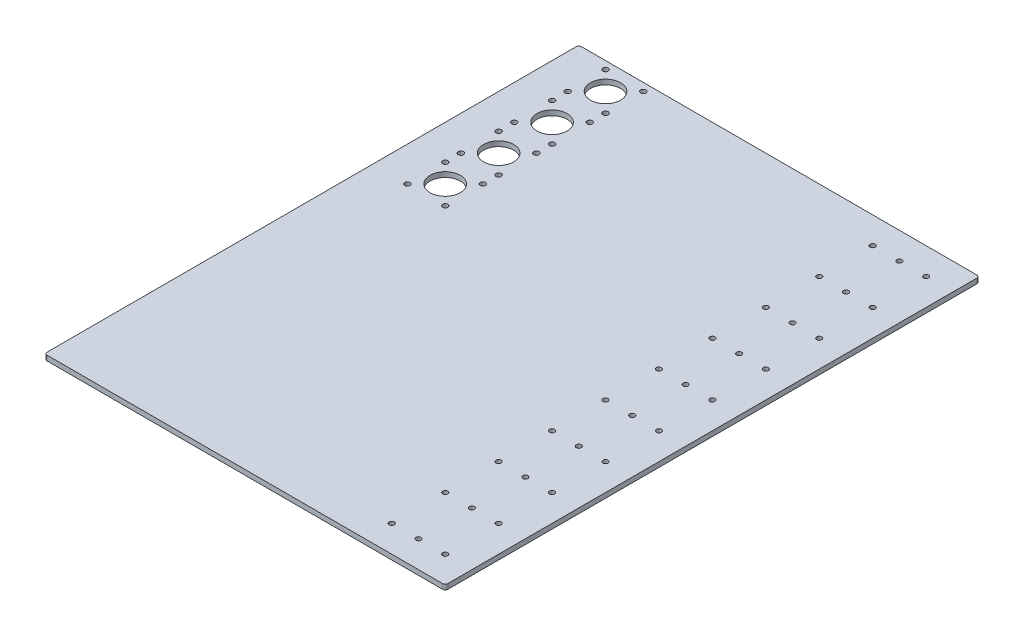
SolidWorks part; units mm, degrees
ref_plane "Front Plane" through (0, 0, 0) normal (0, 0, 1) x (1, 0, 0)
ref_plane "Top Plane" through (0, 0, 0) normal (0, 1, 0) x (1, 0, 0)
ref_plane "Right Plane" through (0, 0, 0) normal (1, 0, 0) x (0, 0, -1)
sketch "Sketch1" plane through (0, 0, 0) normal (0, 1, 0) x (1, 0, 0)
  line L1 (-190.5, 254) -> (190.5, 254)
  line L2 (-190.5, 254) -> (-190.5, -254)
  line L3 (-190.5, -254) -> (190.5, -254)
  line L4 (190.5, 254) -> (190.5, -254)
  line L5 (-190.5, 254) -> (190.5, -254) construction
  line L6 (-190.5, -254) -> (190.5, 254) construction
  point P0 (0, 0)
  dimension "D1" = 508
  dimension "D2" = 381
extrude "Boss-Extrude1" add sketch "Sketch1" along normal blind 4.7625
sketch "Sketch2" plane through (0, 4.7625, 0) normal (0, 1, 0) x (1, 0, 0)
  line L0 (190.5, 254) -> (-190.5, 254) construction
  line L1 (-190.5, 254) -> (-190.5, -254) construction
  circle A0 centre (-139.7, 228.6) radius 14.3383
  circle A2 centre (-157.6605, 246.5605) radius 2.54
  circle A3 centre (-121.7395, 246.5605) radius 2.54
  circle A4 centre (-121.7395, 210.6395) radius 2.54
  circle A5 centre (-157.6605, 210.6395) radius 2.54
  circle A6 centre (-139.7, 177.8) radius 14.3383
  circle A7 centre (-121.7395, 195.7605) radius 2.54
  circle A8 centre (-157.6605, 195.7605) radius 2.54
  circle A9 centre (-157.6605, 159.8395) radius 2.54
  circle A10 centre (-121.7395, 159.8395) radius 2.54
  circle A11 centre (-139.7, 127) radius 14.3383
  circle A12 centre (-121.7395, 144.9605) radius 2.54
  circle A13 centre (-157.6605, 144.9605) radius 2.54
  circle A14 centre (-157.6605, 109.0395) radius 2.54
  circle A15 centre (-121.7395, 109.0395) radius 2.54
  circle A16 centre (-139.7, 76.2) radius 14.3383
  circle A17 centre (-121.7395, 94.1605) radius 2.54
  circle A18 centre (-157.6605, 94.1605) radius 2.54
  circle A19 centre (-157.6605, 58.2395) radius 2.54
  circle A20 centre (-121.7395, 58.2395) radius 2.54
  point P17 (-139.7, 228.6)
  dimension "D2" = 28.6766
  dimension "D3" = 50.8
  dimension "D5" = 5.08
  dimension "D1" = 25.4
  dimension "D4" = 25.4
  dimension "D7" = 4
  dimension "D6" = 4
extrude "Cut-Extrude1" cut sketch "Sketch2" against normal blind 4.7625
sketch "Sketch3" plane through (0, 4.7625, 0) normal (0, 1, 0) x (1, 0, 0)
  line L0 (190.5, -254) -> (190.5, 254) construction
  line L1 (190.5, 254) -> (-190.5, 254) construction
  circle A0 centre (165.1, 228.6) radius 2.413
  circle A1 centre (165.1, 177.8) radius 2.413
  circle A2 centre (165.1, 127) radius 2.413
  circle A3 centre (165.1, 76.2) radius 2.413
  circle A4 centre (165.1, 25.4) radius 2.413
  circle A5 centre (165.1, -25.4) radius 2.413
  circle A6 centre (165.1, -76.2) radius 2.413
  circle A7 centre (165.1, -127) radius 2.413
  circle A8 centre (165.1, -177.8) radius 2.413
  circle A9 centre (165.1, -228.6) radius 2.413
  circle A10 centre (139.7, 177.8) radius 2.413
  circle A11 centre (139.7, 127) radius 2.413
  circle A12 centre (139.7, 76.2) radius 2.413
  circle A13 centre (139.7, 25.4) radius 2.413
  circle A14 centre (139.7, -25.4) radius 2.413
  circle A15 centre (139.7, -76.2) radius 2.413
  circle A16 centre (139.7, -127) radius 2.413
  circle A17 centre (139.7, -177.8) radius 2.413
  circle A18 centre (139.7, -228.6) radius 2.413
  circle A19 centre (114.3, 177.8) radius 2.413
  circle A20 centre (114.3, 127) radius 2.413
  circle A21 centre (114.3, 76.2) radius 2.413
  circle A22 centre (114.3, 25.4) radius 2.413
  circle A23 centre (114.3, -25.4) radius 2.413
  circle A24 centre (114.3, -76.2) radius 2.413
  circle A25 centre (114.3, -127) radius 2.413
  circle A26 centre (114.3, -177.8) radius 2.413
  circle A27 centre (114.3, -228.6) radius 2.413
  circle A28 centre (139.7, 228.6) radius 2.413
  circle A29 centre (114.3, 228.6) radius 2.413
  dimension "D1" = 4.826
  dimension "D2" = 25.4
  dimension "D3" = 25.4
  dimension "D4" = 10
  dimension "D5" = 3
extrude "Cut-Extrude2" cut sketch "Sketch3" against normal blind 4.7625
fillet "Fillet1" radius 2.54 4 edges at (190.5, 2.3813, -254) (190.5, 2.3813, 254) (-190.5, 2.3813, 254) (-190.5, 2.3813, -254)
